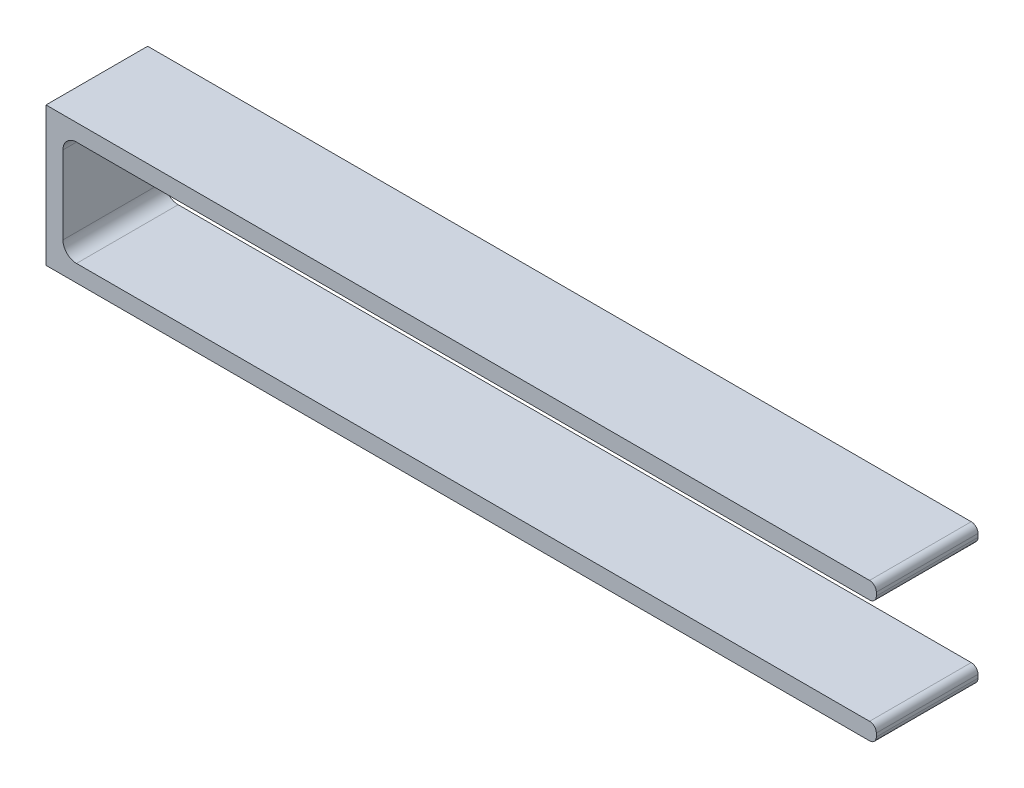
SolidWorks part; units mm, degrees
ref_plane "Front Plane" through (0, 0, 0) normal (0, 0, 1) x (1, 0, 0)
ref_plane "Top Plane" through (0, 0, 0) normal (0, 1, 0) x (1, 0, 0)
ref_plane "Right Plane" through (0, 0, 0) normal (1, 0, 0) x (0, 0, -1)
sketch "Sketch1" plane through (0, 0, 0) normal (0, 0, 1) x (1, 0, 0)
  line L0 (0, 0) -> (0, 15.5)
  line L1 (0, 15.5) -> (119, 15.5)
  line L2 (0, 0) -> (119, 0)
  line L3 (-2.5, -2.5) -> (119, -2.5)
  line L4 (-2.5, -2.5) -> (-2.5, 18)
  line L5 (-2.5, 18) -> (119, 18)
  line L6 (120, 17) -> (120, 16.5)
  line L7 (120, -1) -> (120, -1.5)
  line L8 (-2.5, -2.5) -> (120, -2.5) construction
  line L9 (0, 0) -> (120, 0) construction
  line L10 (-2.5, 18) -> (120, 18) construction
  line L11 (0, 15.5) -> (120, 15.5) construction
  arc A0 (120, -1.5) -> (119, -2.5) centre (119, -1.5) cw
  arc A1 (120, -1) -> (119, 0) centre (119, -1) ccw
  arc A2 (120, 17) -> (119, 18) centre (119, 17) ccw
  arc A3 (119, 15.5) -> (120, 16.5) centre (119, 16.5) ccw
  dimension "D2" = 1
  dimension "D1" = 2.5
extrude "Boss-Extrude1" add sketch "Sketch1" along normal blind 15
fillet "Fillet1" radius 2 2 edges at (0, 0, 7.5) (0, 15.5, 7.5)
